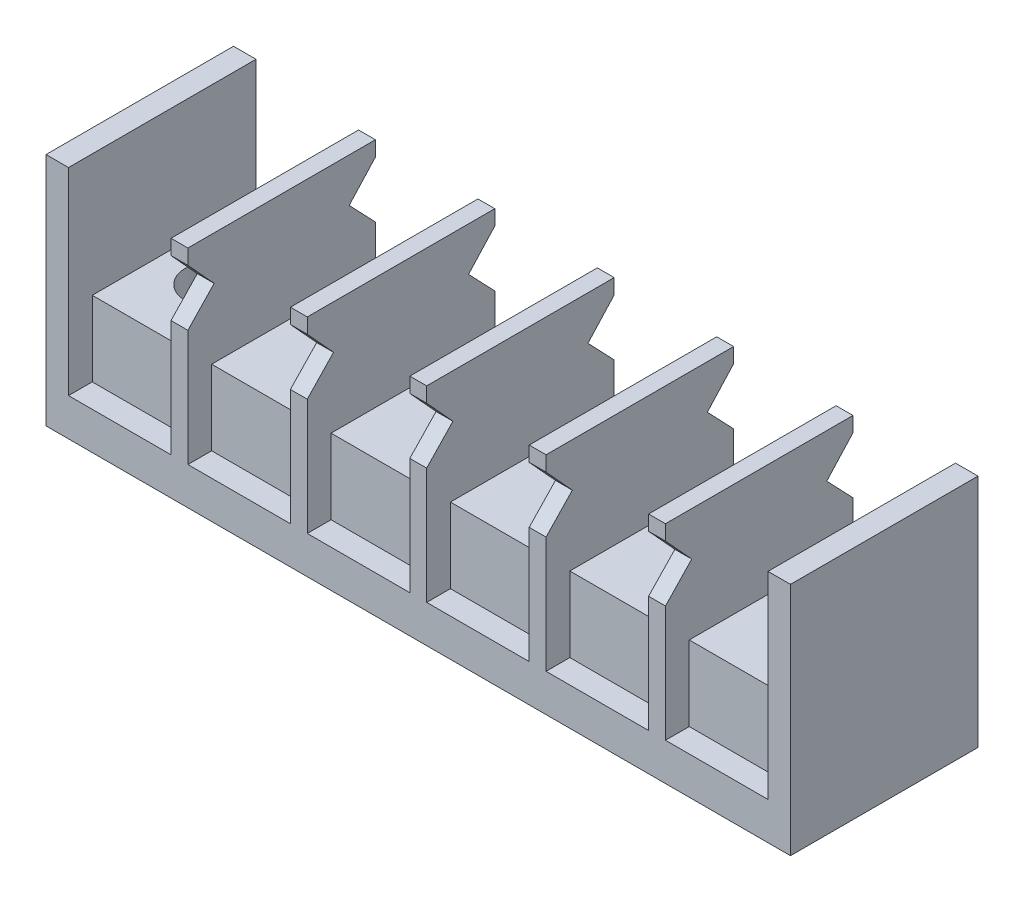
SolidWorks part; units mm, degrees
ref_plane "前视基准面" through (0, 0, 0) normal (0, 0, 1) x (1, 0, 0)
ref_plane "上视基准面" through (0, 0, 0) normal (0, 1, 0) x (1, 0, 0)
ref_plane "右视基准面" through (0, 0, 0) normal (1, 0, 0) x (0, 0, -1)
sketch "草图1" plane through (0, 0, 0) normal (0, 1, 0) x (1, 0, 0)
  line L0 (0, 12.7565) -> (0, -11.1323) construction
  line L1 (-29.775, -7.5) -> (29.775, -7.5)
  line L2 (-29.775, -7.5) -> (-29.775, 7.5)
  line L3 (-29.775, 7.5) -> (29.775, 7.5)
  line L4 (29.775, -7.5) -> (29.775, 7.5)
  line L5 (-29.1602, 0) -> (32.7116, 0) construction
  dimension "D1" = 59.55
  dimension "D2" = 15
extrude "拉伸1" add sketch "草图1" along normal blind 18.8
sketch "草图2" plane through (0, 18.8, 0) normal (0, 1, 0) x (-1, 0, 0)
  line L0 (-29.775, -7.5) -> (29.775, -7.5) construction
  line L1 (-27.975, -7.5) -> (27.975, -7.5)
  line L2 (-27.975, -7.5) -> (-27.975, 7.5)
  line L3 (-27.975, 7.5) -> (27.975, 7.5)
  line L4 (27.975, -7.5) -> (27.975, 7.5)
  line L5 (29.775, 7.5) -> (-29.775, 7.5) construction
  line L6 (-29.775, 7.5) -> (-29.775, -7.5) construction
  line L7 (29.775, -7.5) -> (29.775, 7.5) construction
  dimension "D1" = 1.8
  dimension "D2" = 1.8
extrude "切除-拉伸1" cut sketch "草图2" against normal offset from surface (0.8 mm away) 18 up to face at (0, 0, 0)
sketch "草图4" plane through (0, 18, 0) normal (0, 1, 0) x (-1, 0, 0)
  line L0 (27.975, 7.5) -> (-27.975, 7.5) construction
  line L1 (-27.975, -7.5) -> (-19.775, -7.5)
  line L2 (-27.975, -7.5) -> (-27.975, 7.5)
  line L3 (-27.975, 7.5) -> (-19.775, 7.5)
  line L4 (-19.775, -7.5) -> (-19.775, 7.5)
  line L5 (-18.425, -7.5) -> (-10.225, -7.5)
  line L6 (-18.425, -7.5) -> (-18.425, 7.5)
  line L7 (-18.425, 7.5) -> (-10.225, 7.5)
  line L8 (-10.225, -7.5) -> (-10.225, 7.5)
  line L9 (-8.875, -7.5) -> (-0.675, -7.5)
  line L10 (-8.875, -7.5) -> (-8.875, 7.5)
  line L11 (-8.875, 7.5) -> (-0.675, 7.5)
  line L12 (-0.675, -7.5) -> (-0.675, 7.5)
  line L13 (0.675, -7.5) -> (8.875, -7.5)
  line L14 (0.675, -7.5) -> (0.675, 7.5)
  line L15 (0.675, 7.5) -> (8.875, 7.5)
  line L16 (8.875, -7.5) -> (8.875, 7.5)
  line L17 (10.225, -7.5) -> (18.425, -7.5)
  line L18 (10.225, -7.5) -> (10.225, 7.5)
  line L19 (10.225, 7.5) -> (18.425, 7.5)
  line L20 (18.425, -7.5) -> (18.425, 7.5)
  line L21 (19.775, -7.5) -> (27.975, -7.5)
  line L22 (19.775, -7.5) -> (19.775, 7.5)
  line L23 (19.775, 7.5) -> (27.975, 7.5)
  line L24 (27.975, -7.5) -> (27.975, 7.5)
  dimension "D1" = 8.2
extrude "切除-拉伸2" cut sketch "草图4" against normal offset from surface (9 mm away) 9 up to face at (0, 0, 0)
sketch "草图5" plane through (0, 18, 0) normal (0, 1, 0) x (-1, 0, 0)
  line L1 (27.975, -7.5) -> (27.975, 7.5) construction
  line L2 (19.775, -7.5) -> (27.975, -7.5)
  line L3 (19.775, -7.5) -> (19.775, -5.6)
  line L4 (19.775, -5.6) -> (27.975, -5.6)
  line L5 (29.9336, 0) -> (-26.6321, 0) construction
  line L6 (27.975, -7.5) -> (27.975, -5.6)
  line L7 (27.975, 7.5) -> (27.975, 5.6)
  line L8 (19.775, 5.6) -> (27.975, 5.6)
  line L9 (19.775, 7.5) -> (19.775, 5.6)
  line L10 (19.775, 7.5) -> (27.975, 7.5)
  line L11 (10.225, -7.5) -> (18.425, -7.5)
  line L12 (10.225, -7.5) -> (10.225, -5.6)
  line L13 (10.225, -5.6) -> (18.425, -5.6)
  line L14 (18.425, -7.5) -> (18.425, -5.6)
  line L15 (18.425, 7.5) -> (18.425, 5.6)
  line L16 (10.225, 5.6) -> (18.425, 5.6)
  line L17 (10.225, 7.5) -> (10.225, 5.6)
  line L18 (10.225, 7.5) -> (18.425, 7.5)
  line L19 (0.675, -7.5) -> (8.875, -7.5)
  line L20 (0.675, -7.5) -> (0.675, -5.6)
  line L21 (0.675, -5.6) -> (8.875, -5.6)
  line L22 (8.875, -7.5) -> (8.875, -5.6)
  line L23 (8.875, 7.5) -> (8.875, 5.6)
  line L24 (0.675, 5.6) -> (8.875, 5.6)
  line L25 (0.675, 7.5) -> (0.675, 5.6)
  line L26 (0.675, 7.5) -> (8.875, 7.5)
  line L27 (-8.875, -7.5) -> (-0.675, -7.5)
  line L28 (-8.875, -7.5) -> (-8.875, -5.6)
  line L29 (-8.875, -5.6) -> (-0.675, -5.6)
  line L30 (-0.675, -7.5) -> (-0.675, -5.6)
  line L31 (-0.675, 7.5) -> (-0.675, 5.6)
  line L32 (-8.875, 5.6) -> (-0.675, 5.6)
  line L33 (-8.875, 7.5) -> (-8.875, 5.6)
  line L34 (-8.875, 7.5) -> (-0.675, 7.5)
  line L35 (-18.425, -7.5) -> (-10.225, -7.5)
  line L36 (-18.425, -7.5) -> (-18.425, -5.6)
  line L37 (-18.425, -5.6) -> (-10.225, -5.6)
  line L38 (-10.225, -7.5) -> (-10.225, -5.6)
  line L39 (-10.225, 7.5) -> (-10.225, 5.6)
  line L40 (-18.425, 5.6) -> (-10.225, 5.6)
  line L41 (-18.425, 7.5) -> (-18.425, 5.6)
  line L42 (-18.425, 7.5) -> (-10.225, 7.5)
  line L43 (-27.975, -7.5) -> (-19.775, -7.5)
  line L44 (-27.975, -7.5) -> (-27.975, -5.6)
  line L45 (-27.975, -5.6) -> (-19.775, -5.6)
  line L46 (-19.775, -7.5) -> (-19.775, -5.6)
  line L47 (-19.775, 7.5) -> (-19.775, 5.6)
  line L48 (-27.975, 5.6) -> (-19.775, 5.6)
  line L49 (-27.975, 7.5) -> (-27.975, 5.6)
  line L50 (-27.975, 7.5) -> (-19.775, 7.5)
  dimension "D1" = 11.2
extrude "切除-拉伸3" cut sketch "草图5" against normal offset from surface (15 mm away) 3 up to face at (0, 0, 0)
sketch "草图6" plane through (0, 0, 0) normal (0, -1, 0) x (1, 0, 0)
  line L0 (0, 12.0415) -> (0, -12.1791) construction
  line L1 (32.807, 0) -> (-32.4423, 0) construction
  line L2 (-4.025, 0.375) -> (-5.525, 0.375)
  line L3 (-4.025, 0.375) -> (-4.025, -0.375)
  line L4 (-4.025, -0.375) -> (-5.525, -0.375)
  line L5 (-5.525, 0.375) -> (-5.525, -0.375)
  line L6 (-4.775, 2.675) -> (-4.775, -2.013) construction
  line L7 (5.525, 0.375) -> (4.025, 0.375)
  line L8 (5.525, 0.375) -> (5.525, -0.375)
  line L9 (5.525, -0.375) -> (4.025, -0.375)
  line L10 (4.025, 0.375) -> (4.025, -0.375)
  line L11 (15.075, 0.375) -> (13.575, 0.375)
  line L12 (15.075, 0.375) -> (15.075, -0.375)
  line L13 (15.075, -0.375) -> (13.575, -0.375)
  line L14 (13.575, 0.375) -> (13.575, -0.375)
  line L15 (-13.575, 0.375) -> (-15.075, 0.375)
  line L16 (-13.575, 0.375) -> (-13.575, -0.375)
  line L17 (-13.575, -0.375) -> (-15.075, -0.375)
  line L18 (-15.075, 0.375) -> (-15.075, -0.375)
  line L19 (-14.325, 2.675) -> (-14.325, -2.013) construction
  dimension "D1" = 0.75
  dimension "D2" = 1.5
  dimension "D3" = 4.775
extrude "拉伸2" add sketch "草图6" along normal blind 5.8
sketch "草图7" plane through (0, 9, 0) normal (0, 1, 0) x (-1, 0, 0)
  line L0 (0, -11.8563) -> (0, 13.0369) construction
  line L1 (-28.2468, 0) -> (30.271, 0) construction
  line L4 (-23.875, -9.8031) -> (-23.875, 12.0765) construction
  line L5 (-27.975, 5.6) -> (-27.975, -5.6) construction
  line L6 (-19.775, -5.6) -> (-19.775, 5.6) construction
  circle A0 centre (-23.875, 0) radius 2.25
  circle A1 centre (23.875, 0) radius 2.25
  dimension "D1" = 4.5
extrude "切除-拉伸4" cut sketch "草图7" against normal through all
sketch "草图8" plane through (19.775, 0, 0) normal (1, 0, 0) x (0, 0, -1)
  line L0 (7.5, 16.8) -> (5.4, 14.5)
  line L1 (5.4, 14.5) -> (7.5, 12.3)
  line L3 (7.5, 18) -> (-7.5, 18) construction
  line L4 (0, 21.7575) -> (0, -9.7526) construction
  line L6 (7.5, 18.8) -> (7.5, 0) construction
  line L8 (7.5, 16.8) -> (7.5, 12.3)
  line L9 (-7.5, 16.8) -> (-7.5, 12.3)
  line L10 (-5.4, 14.5) -> (-7.5, 12.3)
  line L11 (-7.5, 16.8) -> (-5.4, 14.5)
  dimension "D1" = 3.5
  dimension "D2" = 4.5
  dimension "D3" = 1.2
extrude "切除-拉伸5" cut sketch "草图8" against normal up to surface (47.75 mm away)
